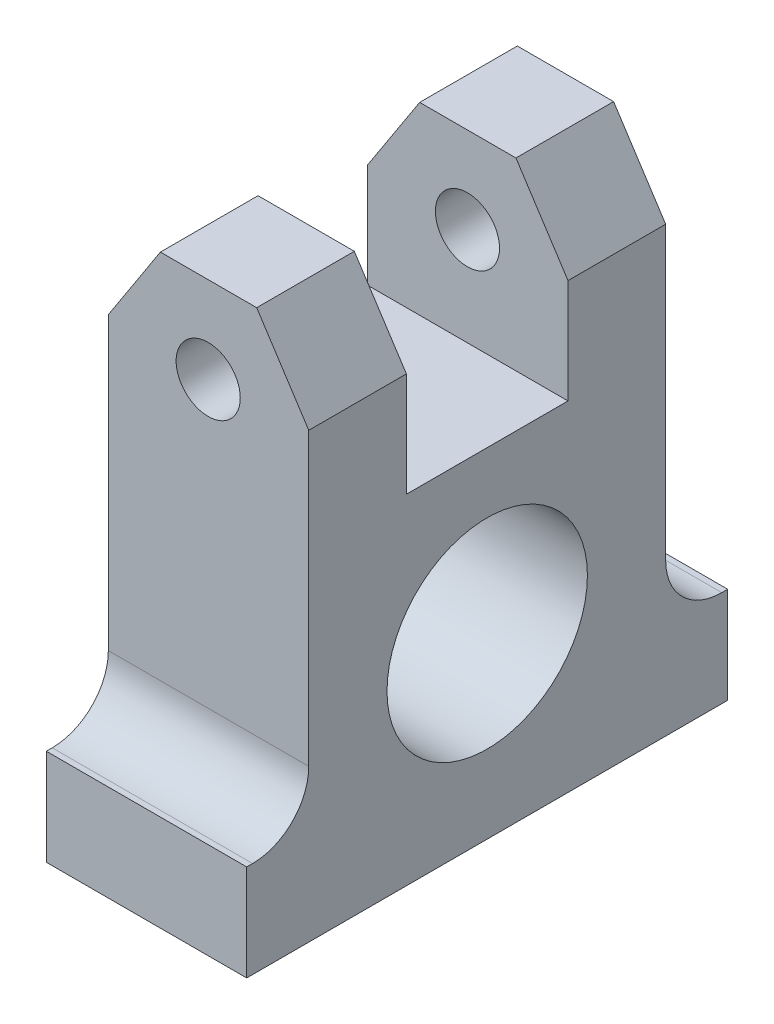
SolidWorks part; units mm, degrees
ref_plane "Спереди" through (0, 0, 0) normal (0, 0, 1) x (1, 0, 0)
ref_plane "Сверху" through (0, 0, 0) normal (0, 1, 0) x (1, 0, 0)
ref_plane "Справа" through (0, 0, 0) normal (1, 0, 0) x (0, 0, -1)
sketch "Эскиз1" plane through (0, 0, 0) normal (1, 0, 0) x (0, 0, -1)
  line L0 (-22.2623, -10.2298) -> (22.2623, -10.2298)
  line L1 (-22.2623, 23.0719) -> (22.2623, 23.0719)
  line L2 (-22.2623, 23.0719) -> (-22.2623, -10.2298)
  line L4 (22.2623, 23.0719) -> (22.2623, -10.2298)
extrude "Вытянуть1" add sketch "Эскиз1" along normal blind 25
sketch "Эскиз2" plane through (0, 23.0719, 0) normal (0, 1, 0) x (1, 0, 0)
  line L1 (0, 22.2623) -> (25, 22.2623)
  line L2 (0, 22.2623) -> (0, -22.2623)
  line L3 (0, -22.2623) -> (25, -22.2623)
  line L4 (25, 22.2623) -> (25, -22.2623)
extrude "Вытянуть2" add sketch "Эскиз2" along normal blind 20
sketch "Эскиз3" plane through (0, 0, 22.2623) normal (0, 0, 1) x (1, 0, 0)
  circle A0 centre (12.4576, 32.2929) radius 4
extrude "Вырез-Вытянуть1" cut sketch "Эскиз3" against normal through all
sketch "Эскиз4" plane through (0, 43.0719, 0) normal (0, 1, 0) x (1, 0, 0)
  line L2 (-28.7925, 10.0803) -> (28.7925, 10.0803)
  line L3 (-28.7925, 10.0803) -> (-28.7925, -10.0803)
  line L4 (-28.7925, -10.0803) -> (28.7925, -10.0803)
  line L6 (28.7925, 10.0803) -> (28.7925, -10.0803)
  line L7 (-28.7925, 10.0803) -> (28.7925, -10.0803) construction
  line L8 (-28.7925, -10.0803) -> (28.7925, 10.0803) construction
  point P0 (0, 0)
extrude "Вырез-Вытянуть2" cut sketch "Эскиз4" against normal blind 23
chamfer "Фаска2" distance 10 angle 33 4 edges at (0, 43.0719, -16.1713) (25, 43.0719, -16.1713) (25, 43.0719, 16.1713) (0, 43.0719, 16.1713)
sketch "Эскиз5" plane through (0, -10.2298, 0) normal (0, -1, 0) x (1, 0, 0)
  line L4 (0, 30) -> (25, 30)
  line L5 (0, 30) -> (0, -30)
  line L6 (0, -30) -> (25, -30)
  line L7 (25, 30) -> (25, -30)
extrude "Вытянуть3" add sketch "Эскиз5" along normal blind 12
fillet "Скругление2" radius 7 2 edges
sketch "Эскиз6" plane through (25, 0, 0) normal (1, 0, 0) x (0, 0, -1)
  circle A0 centre (0, 0) radius 12.5
extrude "Вырез-Вытянуть3" cut sketch "Эскиз6" against normal through all
